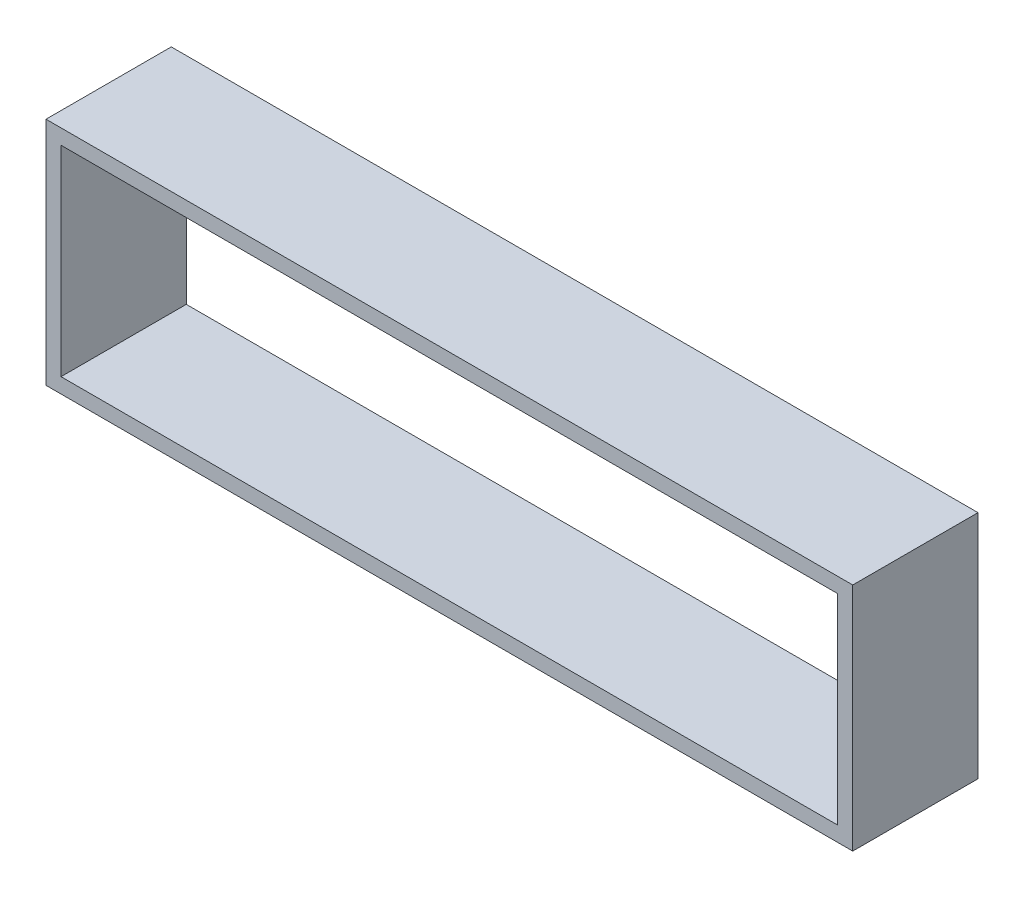
SolidWorks part; units mm, degrees
ref_plane "Спереди" through (0, 0, 0) normal (0, 0, 1) x (1, 0, 0)
ref_plane "Сверху" through (0, 0, 0) normal (0, 1, 0) x (1, 0, 0)
ref_plane "Справа" through (0, 0, 0) normal (1, 0, 0) x (0, 0, -1)
sketch "Эскиз1" plane through (0, 0, 0) normal (0, 0, 1) x (1, 0, 0)
  line L0 (-3, -3) -> (158, -3)
  line L1 (0, 0) -> (155, 0)
  line L2 (0, 0) -> (0, 40)
  line L3 (0, 40) -> (155, 40)
  line L4 (155, 0) -> (155, 40)
  line L5 (158, -3) -> (158, 43)
  line L6 (-3, 43) -> (158, 43)
  line L7 (-3, -3) -> (-3, 43)
  dimension "D1" = 40
  dimension "D2" = 155
  dimension "D3" = 3
extrude "Бобышка-Вытянуть1" add sketch "Эскиз1" along normal blind 25
